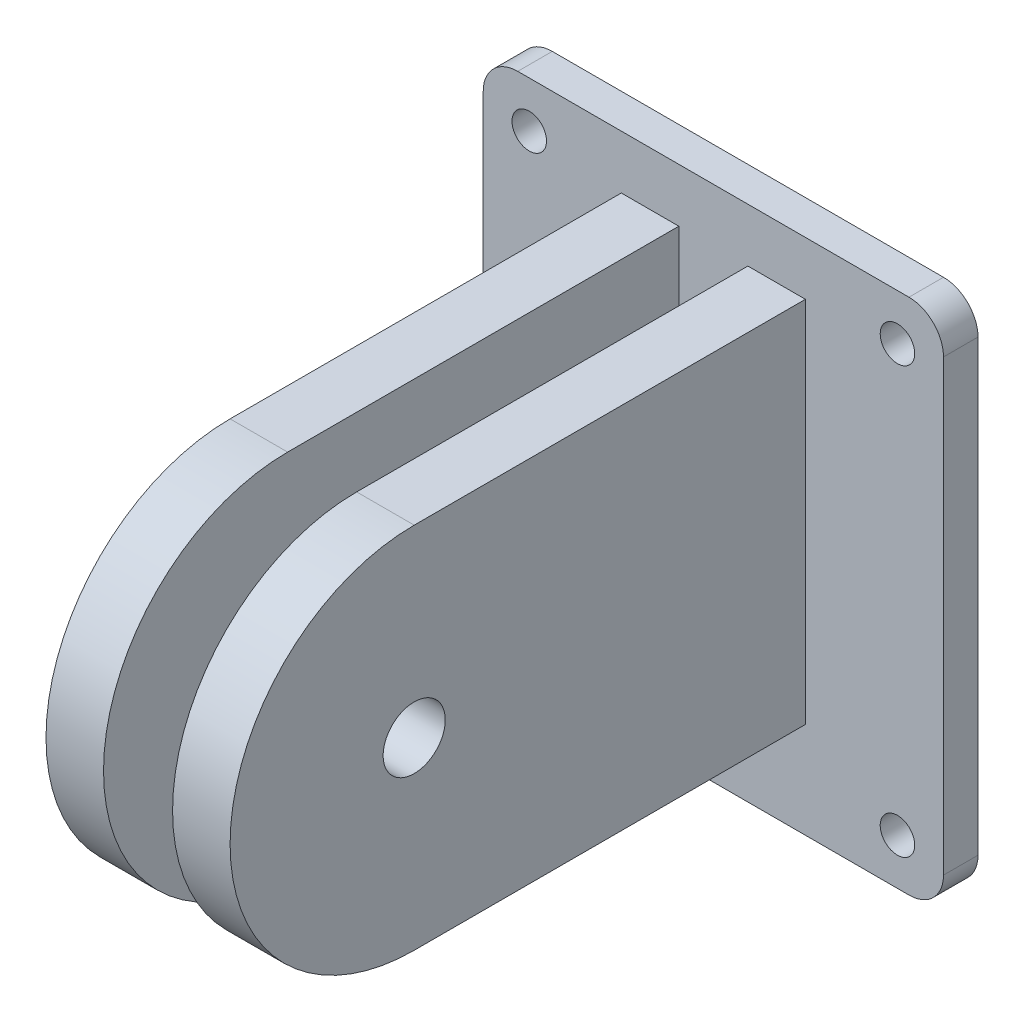
SolidWorks part; units mm, degrees
ref_plane "Front Plane" through (0, 0, 0) normal (0, 0, 1) x (1, 0, 0)
ref_plane "Top Plane" through (0, 0, 0) normal (0, 1, 0) x (1, 0, 0)
ref_plane "Right Plane" through (0, 0, 0) normal (1, 0, 0) x (0, 0, -1)
sketch "Sketch1" plane through (0, 0, 0) normal (0, 0, 1) x (1, 0, 0)
  line L11 (-20, 401.658) -> (20, 401.658)
  line L17 (-20, 401.658) -> (-20, 446.658)
  line L18 (-20, 446.658) -> (20, 446.658)
  line L19 (20, 401.658) -> (20, 446.658)
extrude "Boss-Extrude1" add sketch "Sketch1" along normal blind 3
sketch "Sketch2" plane through (0, 0, 3) normal (0, 0, 1) x (1, 0, 0)
  line L1 (3, 442) -> (8, 442)
  line L2 (3, 442) -> (3, 410)
  line L3 (3, 410) -> (8, 410)
  line L4 (8, 442) -> (8, 410)
  line L6 (-3, 442) -> (-8, 442)
  line L7 (-3, 442) -> (-3, 410)
  line L8 (-3, 410) -> (-8, 410)
  line L9 (-8, 442) -> (-8, 410)
  line L11 (8, 438.658) -> (8, 446.658) construction
  line L12 (20, 446.658) -> (-20, 446.658) construction
  dimension "D1" = 5
  dimension "D2" = 5
  dimension "D3" = 32
  dimension "D4" = 32
  dimension "D5" = 8
extrude "Boss-Extrude2" add sketch "Sketch2" along normal blind 50
sketch "Sketch3" plane through (8, 0, 0) normal (1, 0, 0) x (0, 0, -1)
  line L0 (-53, 426) -> (-37, 426) construction
  line L1 (-53, 410) -> (-53, 442) construction
  line L2 (-37, 442) -> (-57.9042, 442)
  line L3 (-57.9042, 442) -> (-57.9042, 410)
  line L4 (-57.9042, 410) -> (-37, 410)
  arc A0 (-37, 442) -> (-37, 410) centre (-37, 426) ccw
  circle A2 centre (-37, 426) radius 2.7
  dimension "D1" = 16
extrude "Cut-Extrude1" cut sketch "Sketch3" against normal through all
fillet "Fillet2" radius 3 4 edges at (-20, 401.658, 1.5) (-20, 446.658, 1.5) (20, 401.658, 1.5) (20, 446.658, 1.5)
sketch "Sketch4" plane through (0, 0, 3) normal (0, 0, 1) x (1, 0, 0)
  line L0 (17, 446.658) -> (-17, 446.658) construction
  line L1 (-20, 443.658) -> (-20, 404.658) construction
  line L2 (-20, 424.158) -> (0, 424.158) construction
  line L4 (0, 424.158) -> (0, 446.658) construction
  circle A1 centre (-16, 442.658) radius 1.5
  circle A2 centre (-16, 405.658) radius 1.5
  circle A3 centre (16, 405.658) radius 1.5
  circle A4 centre (16, 442.658) radius 1.5
  dimension "D1" = 16
  dimension "D2" = 18.5
extrude "Cut-Extrude2" cut sketch "Sketch4" against normal through all
